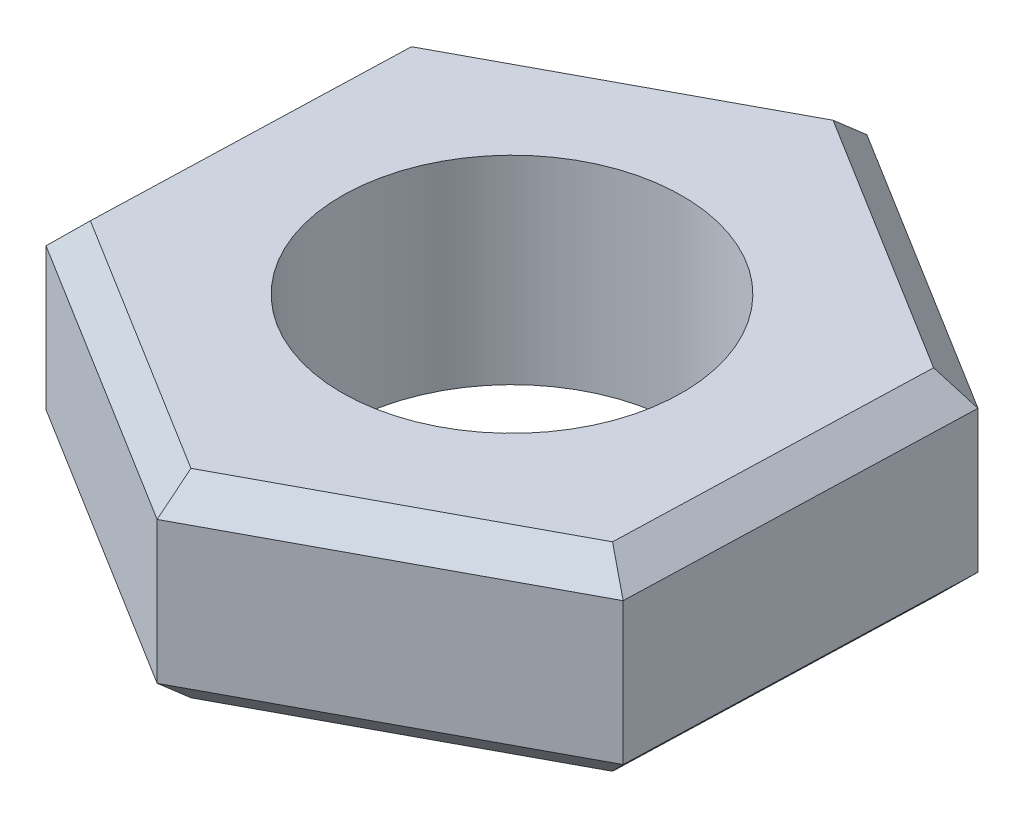
SolidWorks part; units mm, degrees
ref_plane "前视基准面" through (0, 0, 0) normal (0, 0, 1) x (1, 0, 0)
ref_plane "上视基准面" through (0, 0, 0) normal (0, 1, 0) x (1, 0, 0)
ref_plane "右视基准面" through (0, 0, 0) normal (1, 0, 0) x (0, 0, -1)
sketch "草图1" plane through (0, 0, 0) normal (0, 1, 0) x (1, 0, 0)
  line L1 (10.304, -6.3896) -> (10.6856, 5.7287)
  line L2 (10.6856, 5.7287) -> (0.3816, 12.1183)
  line L3 (0.3816, 12.1183) -> (-10.304, 6.3896)
  line L4 (-10.304, 6.3896) -> (-10.6856, -5.7287)
  line L5 (-10.6856, -5.7287) -> (-0.3816, -12.1183)
  line L6 (-0.3816, -12.1183) -> (10.304, -6.3896)
  circle A0 centre (0, 0) radius 10.5 construction
  circle A1 centre (0, 0) radius 6
  dimension "D2" = 12
  dimension "D1" = 21
extrude "拉伸1" add sketch "草图1" along normal blind 7
chamfer "倒角1" distance 1 angle 45 12 edges at (10.4948, 0, 0.3305) (5.5336, 0, -8.9235) (-4.9612, 0, -9.254) (-10.4948, 0, -0.3305) (-5.5336, 0, 8.9235) (4.9612, 0, 9.254) (4.9612, 7, 9.254) (10.4948, 7, 0.3305) (5.5336, 7, -8.9235) (-4.9612, 7, -9.254) (-10.4948, 7, -0.3305) (-5.5336, 7, 8.9235)
